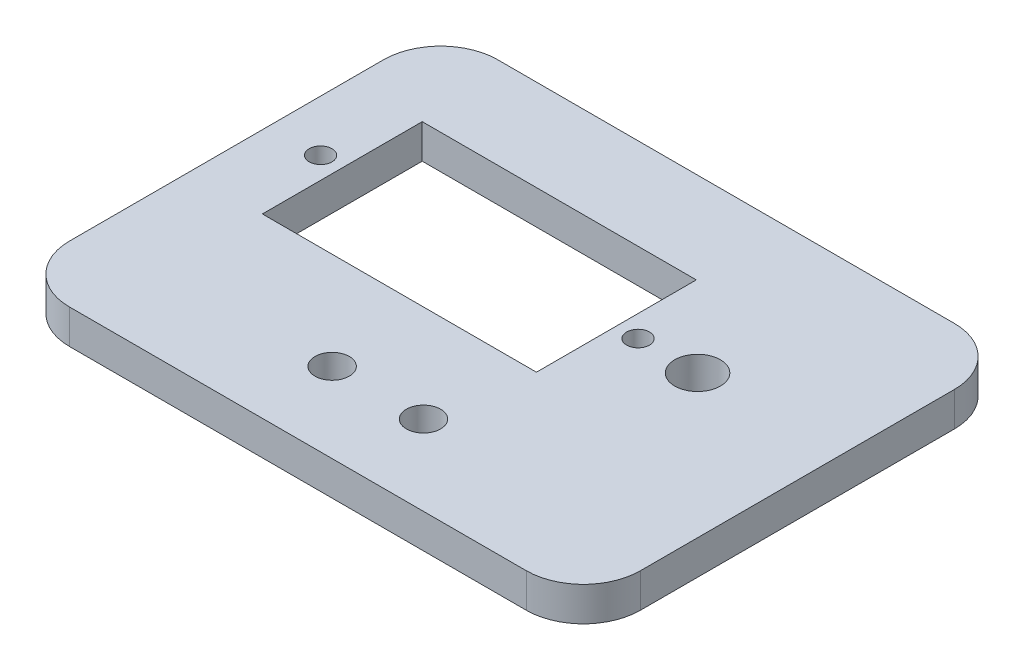
SolidWorks part; units mm, degrees
material "Thornel Mat VMA"
ref_plane "前视基准面" through (0, 0, 0) normal (0, 0, 1) x (1, 0, 0)
ref_plane "上视基准面" through (0, 0, 0) normal (0, 1, 0) x (1, 0, 0)
ref_plane "右视基准面" through (0, 0, 0) normal (1, 0, 0) x (0, 0, -1)
other "Configuration Table"
sketch "草图1" plane through (0, 0, 0) normal (0, 1, 0) x (1, 0, 0)
  line L0 (0, 0) -> (0, 15.9416) construction
  line L1 (-25, -18.75) -> (25, -18.75)
  line L2 (-25, -18.75) -> (-25, 18.75)
  line L3 (-25, 18.75) -> (25, 18.75)
  line L4 (25, -18.75) -> (25, 18.75)
  line L5 (-25, -18.75) -> (25, 18.75) construction
  line L6 (-25, 18.75) -> (25, -18.75) construction
  line L7 (0, 3.75) -> (40.3181, 3.75) construction
  line L8 (-6.61, 3.75) -> (-6.61, 28.1343) construction
  line L9 (-18.61, -3.25) -> (5.39, -3.25)
  line L10 (-18.61, -3.25) -> (-18.61, 10.75)
  line L11 (-18.61, 10.75) -> (5.39, 10.75)
  line L12 (5.39, -3.25) -> (5.39, 10.75)
  line L13 (-18.61, -3.25) -> (5.39, 10.75) construction
  line L14 (-18.61, 10.75) -> (5.39, -3.25) construction
  line L15 (-12.5, 3.75) -> (-12.5, 26.8571) construction
  line L16 (10, 3.75) -> (10, 32.4226) construction
  circle A6 centre (4, -11.75) radius 1.5
  circle A7 centre (-4, -11.75) radius 1.5
  circle A8 centre (7.29, 3.75) radius 1
  circle A9 centre (-20.51, 3.75) radius 1
  point P0 (0, 0)
  point P14 (-6.61, 3.75)
  dimension "D3" = 3
  dimension "D4" = 8
  dimension "D5" = 7
  dimension "D11" = 8.01
  dimension "D12" = 27.8
  dimension "D8" = 2
  dimension "D1" = 50
  dimension "D2" = 37.5
  dimension "D6" = 24
  dimension "D7" = 14
  dimension "D9" = 12.5
  dimension "D10" = 15
  dimension "D14" = 10
extrude "凸台-拉伸1" add sketch "草图1" along normal blind 3
fillet "圆角1" radius 5 4 edges at (-25, 1.5, -18.75) (25, 1.5, -18.75) (25, 1.5, 18.75) (-25, 1.5, 18.75)
sketch "草图2" plane through (0, 3, 0) normal (0, 1, 0) x (1, 0, 0)
  line L0 (7.29, 3.75) -> (42.087, 3.75) construction
  line L1 (5.39, -3.25) -> (5.39, 10.75) construction
  circle A0 centre (12.5, 3.75) radius 2
  dimension "D1" = 4
  dimension "D2" = 7.11
extrude "切除-拉伸1" cut sketch "草图2" against normal blind 10
